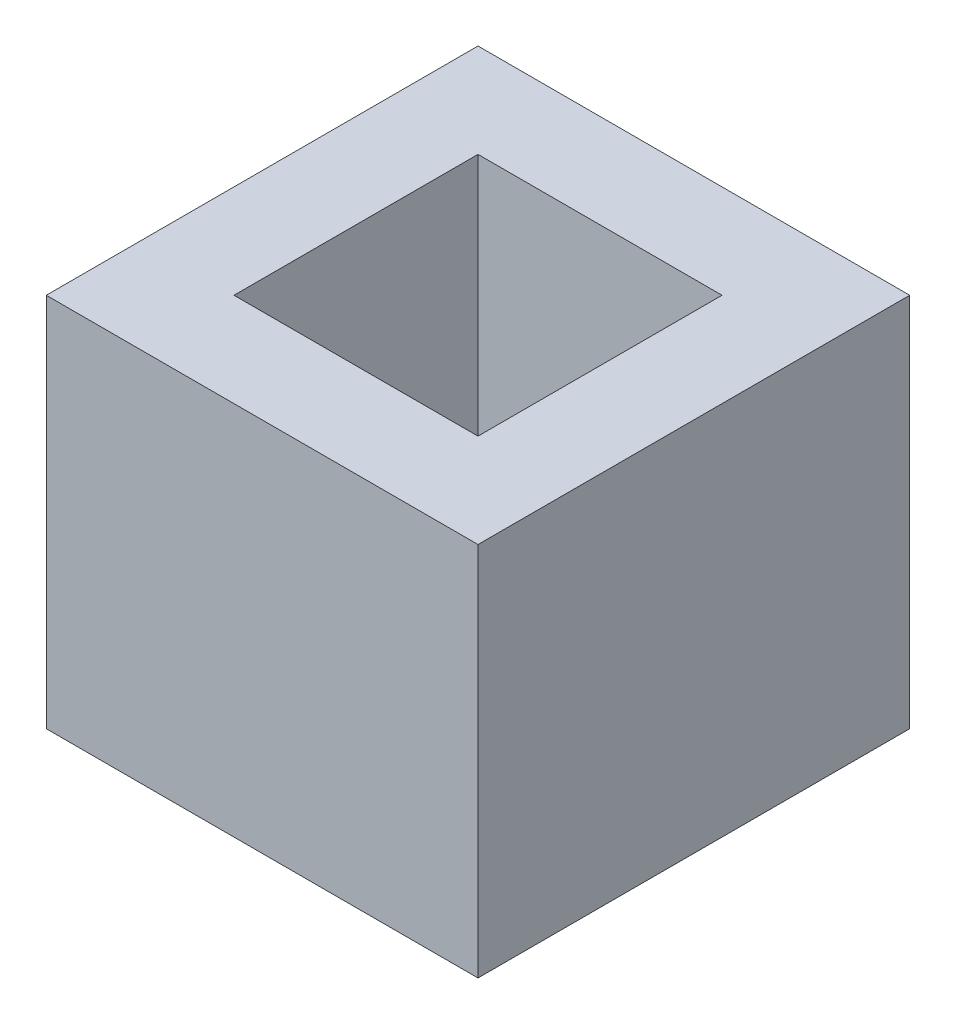
SolidWorks part; units mm, degrees
ref_plane "前视基准面" through (0, 0, 0) normal (0, 0, 1) x (1, 0, 0)
ref_plane "上视基准面" through (0, 0, 0) normal (0, 1, 0) x (1, 0, 0)
ref_plane "右视基准面" through (0, 0, 0) normal (1, 0, 0) x (0, 0, -1)
sketch "草图3" plane through (0, 0, 0) normal (0, 1, 0) x (1, 0, 0)
  line L1 (0, 0) -> (23, 0)
  line L2 (0, 0) -> (0, -23)
  line L3 (0, -23) -> (23, -23)
  line L4 (23, 0) -> (23, -23)
  line L5 (5, -5) -> (18, -5)
  line L6 (5, -5) -> (5, -18)
  line L7 (5, -18) -> (18, -18)
  line L8 (18, -5) -> (18, -18)
  point P9 (0, 0)
  dimension "D1" = 23
  dimension "D2" = 23
  dimension "D3" = 13
  dimension "D4" = 13
extrude "凸台-拉伸3" add sketch "草图3" along normal blind 20
